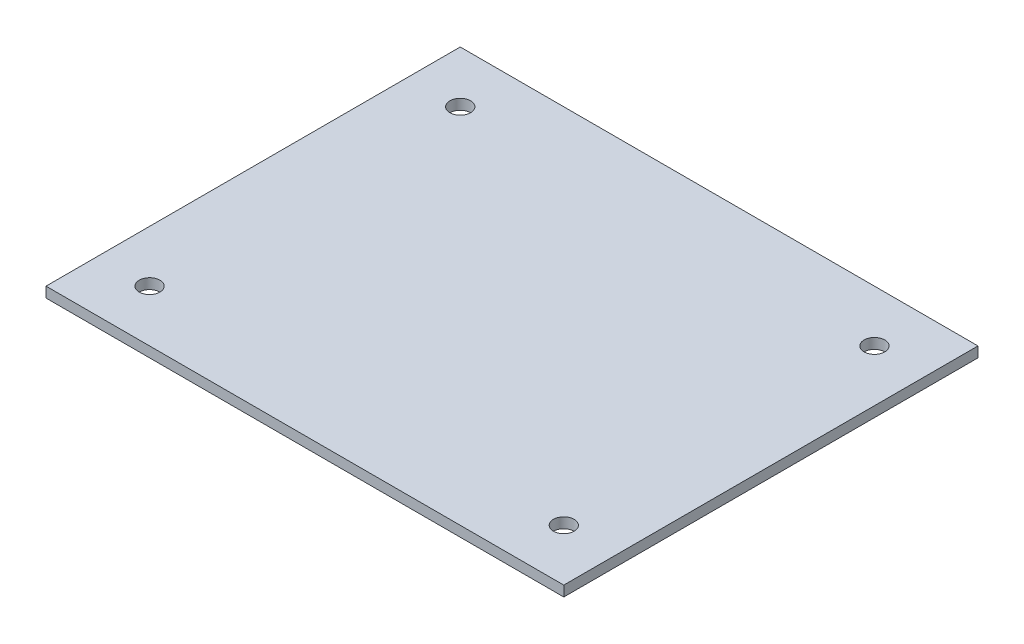
SolidWorks part; units mm, degrees
ref_plane "Front" through (0, 0, 0) normal (0, 0, 1) x (1, 0, 0)
ref_plane "Top" through (0, 0, 0) normal (0, 1, 0) x (1, 0, 0)
ref_plane "Right" through (0, 0, 0) normal (1, 0, 0) x (0, 0, -1)
sketch "Sketch1" plane through (0, 0, 0) normal (0, 1, 0) x (1, 0, 0)
  line L0 (0, 0) -> (-128.646, 0) construction
  line L5 (-125, 100) -> (125, 100)
  line L6 (-125, 100) -> (-125, -100)
  line L7 (-125, -100) -> (125, -100)
  line L8 (125, 100) -> (125, -100)
  line L9 (0, 0) -> (0, 100) construction
  line L10 (-87.1729, -31.3286) -> (-90.8865, -31.4428) construction
  line L11 (-90.0919, -36.3793) -> (-90.8865, -31.4428) construction
  line L12 (75.845, -36.845) -> (75.5776, -36.6214) construction
  line L13 (-90, 0) -> (-77.4344, 0) construction
  line L14 (-75.2357, -51.3853) -> (-66.4611, -50.7048) construction
  line L15 (-90.0919, -36.3793) -> (-86.3053, -35.7698) construction
  line L16 (-87.1696, -31.3285) -> (-90.8865, -31.4428) construction
  line L17 (-90.0919, -36.3793) -> (-90.8865, -31.4428) construction
  line L18 (-90.0919, -36.3793) -> (-86.2961, -35.7683) construction
  line L19 (-26.936, -78.9229) -> (-31.9353, -79.0035) construction
  line L20 (-32.0003, -74.971) -> (-31.9353, -79.0035) construction
  line L21 (-26.936, -78.9229) -> (-31.9353, -79.0035) construction
  line L22 (-32.0003, -74.971) -> (-31.9353, -79.0035) construction
  line L23 (-27.9763, -76.4321) -> (-26.9766, -76.4032) construction
  line L24 (-26.9766, -76.4032) -> (-26.936, -78.9229) construction
  line L25 (-27.9763, -76.4321) -> (-28.0019, -74.8419) construction
  line L26 (-27.9763, -76.4321) -> (-26.9766, -76.4032) construction
  line L27 (-26.9766, -76.4032) -> (-26.936, -78.9229) construction
  line L28 (-27.9763, -76.4321) -> (-28.0019, -74.8419) construction
  arc A0 (-90, 0) -> (-87.1696, -31.3285) centre (82.9375, -0.168) ccw construction
  arc A1 (-82.4604, -50.6749) -> (-78.4781, -55.1627) centre (-75.569, -48.5705) ccw construction
  arc A2 (-70.6654, -56.4296) -> (-72.5022, -56.2312) centre (-72.6533, -66.23) ccw construction
  arc A3 (-70.6654, -56.4296) -> (-62.6819, -65.4755) centre (-72.6534, -66.23) cw construction
  arc A4 (-78.4781, -55.1627) -> (-72.5022, -56.2312) centre (-73.2944, -43.4162) ccw construction
  arc A5 (75.7913, -28.3987) -> (75.7113, -36.7332) centre (80.0932, -32.6077) cw construction
  arc A6 (-62.6819, -65.4755) -> (-54.8607, -73.7223) centre (-53.7075, -64.7965) ccw construction
  arc A7 (-54.8607, -73.7223) -> (-32.0003, -74.971) centre (-35.0001, 80.0002) ccw construction
  arc A8 (-86, -0.0039) -> (-78.6348, -49.5067) centre (82.9375, -0.168) ccw construction
  arc A9 (-78.6348, -49.5067) -> (-76.8631, -51.5032) centre (-75.569, -48.5705) ccw construction
  arc A10 (-76.8631, -51.5032) -> (-72.6226, -52.2301) centre (-73.2944, -43.4162) ccw construction
  arc A11 (-69.8702, -52.5095) -> (-72.6226, -52.2301) centre (-72.6533, -66.23) ccw construction
  arc A12 (-69.8702, -52.5095) -> (-58.6933, -65.1737) centre (-72.6534, -66.23) cw construction
  arc A13 (-58.6933, -65.1737) -> (-54.3482, -69.7553) centre (-53.7075, -64.7965) ccw construction
  arc A14 (-54.3482, -69.7553) -> (72.9322, -25.6013) centre (-35.0001, 80.0002) ccw construction
  arc A15 (72.9322, -25.6013) -> (72.799, -39.4752) centre (80.0932, -32.6077) cw construction
  arc A16 (-77.4344, 0) -> (-64.0038, -46.5641) centre (10, 0) ccw construction
  arc A17 (-66.4611, -50.7048) -> (-64.0038, -46.5641) centre (-66.6886, -47.7703) ccw construction
  arc A18 (-75.2357, -51.3853) -> (-78.6348, -49.5067) centre (-75.5087, -47.8649) cw construction
  arc A19 (-86.2961, -35.7683) -> (-82.4604, -50.6749) centre (82.9375, -0.168) ccw construction
  arc A20 (-28.0019, -74.8419) -> (75.7913, -28.3987) centre (-35.0001, 80.0002) ccw construction
  arc A21 (-90, 0) -> (-82.4604, -50.6749) centre (82.9375, -0.168) ccw construction
  arc A23 (-54.8607, -73.7223) -> (75.7913, -28.3987) centre (-35.0001, 80.0002) ccw construction
  point P4 (125, 0)
  point P9 (0, 100)
  dimension "D1" = 200
  dimension "D2" = 250
  dimension "D3" = 4
extrude "Boss-Extrude1" add sketch "Sketch1" along normal blind 5
sketch "Sketch2" plane through (0, 5, 0) normal (0, 1, 0) x (1, 0, 0)
  line L0 (-90, 0) -> (-77.4344, 0) construction
  line L1 (-75.2357, -51.3853) -> (-66.4611, -50.7048) construction
  line L2 (-90, 0) -> (-77.4344, 0)
  line L3 (-72.6618, -51.1857) -> (-66.4611, -50.7048)
  line L4 (-90.0919, -36.3793) -> (-90.8865, -31.4428) construction
  line L5 (-90.0919, -36.3793) -> (-86.2961, -35.7683) construction
  line L6 (-87.1696, -31.3285) -> (-90.8865, -31.4428) construction
  line L7 (-90.0919, -36.3793) -> (-90.8865, -31.4428)
  line L8 (-90.0919, -36.3793) -> (-86.2961, -35.7683)
  line L9 (-87.1696, -31.3285) -> (-90.8865, -31.4428)
  line L10 (-26.936, -78.9229) -> (-31.9353, -79.0035) construction
  line L11 (-26.9766, -76.4032) -> (-26.936, -78.9229) construction
  line L12 (-27.9763, -76.4321) -> (-26.9766, -76.4032) construction
  line L13 (-27.9763, -76.4321) -> (-28.0019, -74.8419) construction
  line L15 (-26.936, -78.9229) -> (-31.9353, -79.0035)
  line L16 (-26.9766, -76.4032) -> (-26.936, -78.9229)
  line L17 (-27.9763, -76.4321) -> (-26.9766, -76.4032)
  line L18 (-27.9763, -76.4321) -> (-28.0019, -74.8419)
  line L20 (-32.0003, -74.971) -> (-31.9353, -79.0035)
  arc A0 (75.7113, -36.7332) -> (75.7913, -28.3987) centre (80.0932, -32.6077) ccw construction
  arc A2 (-62.6819, -65.4755) -> (-54.8607, -73.7223) centre (-53.7075, -64.7965) ccw construction
  arc A3 (-62.6819, -65.4755) -> (-70.6654, -56.4296) centre (-72.6534, -66.23) ccw construction
  arc A4 (-70.6654, -56.4296) -> (-72.5022, -56.2312) centre (-72.6533, -66.23) ccw construction
  arc A5 (-78.4781, -55.1627) -> (-72.5022, -56.2312) centre (-73.2944, -43.4162) ccw construction
  arc A6 (-82.4604, -50.6749) -> (-78.4781, -55.1627) centre (-75.569, -48.5705) ccw construction
  arc A8 (-77.4344, 0) -> (-64.0038, -46.5641) centre (10, 0) ccw construction
  arc A9 (-66.4611, -50.7048) -> (-64.0038, -46.5641) centre (-66.6886, -47.7703) ccw construction
  arc A10 (-86.2961, -35.7683) -> (-82.4604, -50.6749) centre (82.9375, -0.168) ccw
  arc A11 (75.7113, -36.7332) -> (75.7913, -28.3987) centre (80.0932, -32.6077) ccw
  arc A12 (-54.8607, -73.7223) -> (-32.0003, -74.971) centre (-35.0001, 80.0002) ccw
  arc A13 (-62.6819, -65.4755) -> (-54.8607, -73.7223) centre (-53.7075, -64.7965) ccw
  arc A14 (-62.6819, -65.4755) -> (-70.6654, -56.4296) centre (-72.6534, -66.23) ccw
  arc A15 (-70.6654, -56.4296) -> (-72.5022, -56.2312) centre (-72.6533, -66.23) ccw
  arc A16 (-78.4781, -55.1627) -> (-72.5022, -56.2312) centre (-73.2944, -43.4162) ccw
  arc A17 (-82.4604, -50.6749) -> (-78.4781, -55.1627) centre (-75.569, -48.5705) ccw
  arc A18 (-90, 0) -> (-87.1696, -31.3285) centre (82.9375, -0.168) ccw
  arc A19 (-77.4344, 0) -> (-64.0038, -46.5641) centre (10, 0) ccw
  arc A20 (-66.4611, -50.7048) -> (-64.0038, -46.5641) centre (-66.6886, -47.7703) ccw
  arc A22 (72.799, -39.4752) -> (72.9322, -25.6013) centre (80.0932, -32.6077) ccw construction
  arc A23 (-54.3482, -69.7553) -> (72.9322, -25.6013) centre (-35.0001, 80.0002) ccw construction
  arc A24 (-58.6933, -65.1737) -> (-54.3482, -69.7553) centre (-53.7075, -64.7965) ccw construction
  arc A25 (-58.6933, -65.1737) -> (-69.8702, -52.5095) centre (-72.6534, -66.23) ccw construction
  arc A26 (-69.8702, -52.5095) -> (-72.6226, -52.2301) centre (-72.6533, -66.23) ccw construction
  arc A27 (-28.0019, -74.8419) -> (75.7913, -28.3987) centre (-35.0001, 80.0002) ccw
  arc A28 (72.799, -39.4752) -> (72.9322, -25.6013) centre (80.0932, -32.6077) ccw
  arc A29 (-54.3482, -69.7553) -> (72.9322, -25.6013) centre (-35.0001, 80.0002) ccw
  arc A30 (-58.6933, -65.1737) -> (-54.3482, -69.7553) centre (-53.7075, -64.7965) ccw
  arc A31 (-58.6933, -65.1737) -> (-69.8702, -52.5095) centre (-72.6534, -66.23) ccw
  arc A32 (-69.8702, -52.5095) -> (-72.6226, -52.2301) centre (-72.6533, -66.23) ccw
  arc A34 (72.799, -39.4752) -> (75.7113, -36.7332) centre (74.2551, -38.1042) cw
  arc A37 (-72.6226, -52.2301) -> (-72.6618, -51.1857) centre (-72.6214, -51.7071) cw
  dimension "D1" = 0.523
extrude "Cut-Extrude1" [suppressed] cut sketch "Sketch2" against normal through all
mirror "Mirror1" [suppressed]
sketch "Sketch3" plane through (0, 0, 0) normal (0, 1, 0) x (1, 0, 0)
  line L0 (0, 0) -> (-155.8079, 0) construction
  line L1 (0, 0) -> (0, 127.5715) construction
  circle A0 centre (-100, 75) radius 5
  circle A1 centre (100, 75) radius 5
  circle A2 centre (100, -75) radius 5
  circle A3 centre (-100, -75) radius 5
  dimension "D1" = 10
  dimension "D2" = 150
  dimension "D3" = 200
extrude "holes" cut sketch "Sketch3" along normal through all
